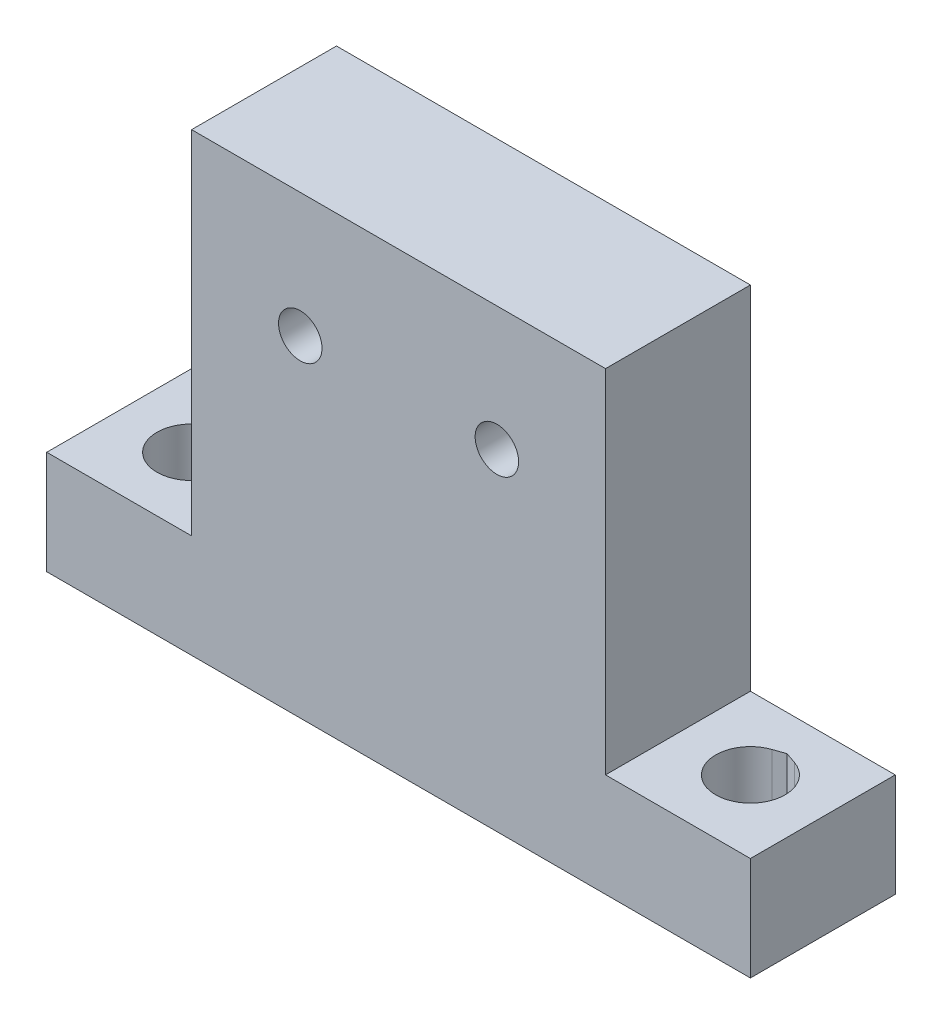
SolidWorks part; units mm, degrees
ref_plane "Frontal Plane" through (0, 0, 0) normal (0, 0, 1) x (1, 0, 0)
ref_plane "Horizontal Plane" through (0, 0, 0) normal (0, 1, 0) x (1, 0, 0)
ref_plane "Profile Plane" through (0, 0, 0) normal (1, 0, 0) x (0, 0, -1)
sketch "Sketch2" plane through (0, 0, 0) normal (0, 0, 1) x (1, 0, 0)
  line L0 (-10, 5) -> (-17, 5)
  line L2 (-10, 5) -> (-10, 22)
  line L5 (-17, 5) -> (-17, 0)
  line L6 (-17, 0) -> (17, 0)
  line L7 (-10, 22) -> (10, 22)
  line L8 (0, 22) -> (0, 0) construction
  line L9 (17, 5) -> (17, 0)
  line L10 (10, 5) -> (10, 22)
  line L11 (10, 5) -> (17, 5)
  circle A0 centre (-4.75, 16) radius 1.05
  circle A2 centre (4.75, 16) radius 1.05
  dimension "D1" = 2.1
  dimension "D2" = 5
  dimension "D3" = 7
  dimension "D4" = 9.5
  dimension "D5" = 20
  dimension "D6" = 6
  dimension "D7" = 22
extrude "Boss-Extrude1" add sketch "Sketch2" along normal blind 7
sketch "Sketch3" plane through (0, 5, 0) normal (0, 1, 0) x (1, 0, 0)
  line L0 (-17, -7) -> (-17, 0) construction
  line L1 (-10, 0) -> (-17, 0) construction
  line L3 (-13.5, -3.5) -> (-13.5, -1.7267) construction
  line L4 (-13.5, -1.7267) -> (-12.95, -1.9179)
  line L5 (-13.5, -1.7267) -> (-14.05, -1.9179)
  line L6 (0, 0) -> (0, -7) construction
  line L7 (10, 0) -> (-10, 0) construction
  line L8 (10, -7) -> (-10, -7) construction
  line L9 (13.5, -3.5) -> (13.5, -1.7267) construction
  line L10 (13.5, -1.7267) -> (14.05, -1.9179)
  line L11 (13.5, -1.7267) -> (12.95, -1.9179)
  arc A0 (-14.05, -1.9179) -> (-12.95, -1.9179) centre (-13.5, -3.5) ccw
  arc A1 (14.05, -1.9179) -> (12.95, -1.9179) centre (13.5, -3.5) cw
  point P7 (-17, -3.5)
  point P11 (-13.5, 0)
  dimension "D1" = 3.35
  dimension "D2" = 0.55
extrude "Cut-Extrude1" cut sketch "Sketch3" against normal through all
